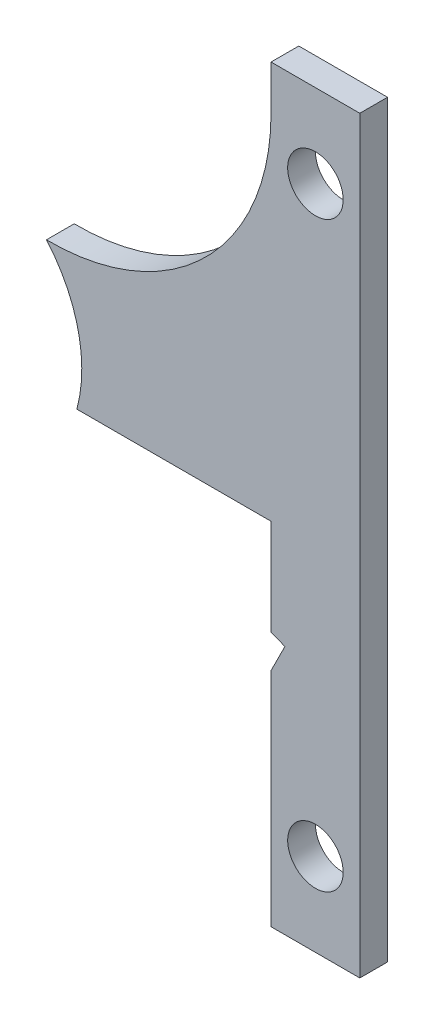
SolidWorks part; units mm, degrees
ref_plane "Front Plane" through (0, 0, 0) normal (0, 0, 1) x (1, 0, 0)
ref_plane "Top Plane" through (0, 0, 0) normal (0, 1, 0) x (1, 0, 0)
ref_plane "Right Plane" through (0, 0, 0) normal (1, 0, 0) x (0, 0, -1)
sketch "Sketch4" plane through (0, 0, 0) normal (0, 0, 1) x (1, 0, 0)
  line L9 (0, -70) -> (60, -70) construction
  line L10 (25, -6.6987) -> (60, -6.6987)
  line L11 (60, -24.0119) -> (60, -6.6987)
  line L12 (0, -70) -> (0, 0) construction
  line L13 (60, 57) -> (20, 57) construction
  line L15 (62.5, -25) -> (60, -24.0119)
  line L16 (60, -30) -> (62.5, -25)
  line L17 (60, -70) -> (60, -30)
  line L18 (76, -70) -> (60, -70)
  line L19 (76, 62) -> (76, -70)
  line L20 (60, 62) -> (76, 62) construction
  line L21 (60, 57) -> (60, 62)
  line L23 (0, 0) -> (25, -6.6987) construction
  line L24 (0, 0) -> (20, 16.782) construction
  line L25 (20, 16.782) -> (20, 57) construction
  line L26 (60, 62) -> (60, 65)
  line L27 (60, 65) -> (76, 65)
  line L28 (76, 65) -> (76, 62)
  circle A6 centre (0, 0) radius 25 construction
  arc A10 (25, -6.6987) -> (19.5134, 17.003) centre (0, 0) ccw
  arc A13 (60, 57) -> (19.5134, 17.003) centre (20, 57) cw
  dimension "D5" = 16
  dimension "D6" = 16
  dimension "D9" = 75
  dimension "D16" = 2.5
  dimension "D1" = 50
  dimension "D8" = 35
  dimension "D11" = 55
  dimension "D10" = 40
  dimension "D2" = 132
  dimension "D3" = 70
  dimension "D4" = 60
  dimension "D7" = 5
  dimension "D12" = 3
  dimension "D13" = 40
  dimension "D14" = 5
  dimension "D15" = 85
extrude "Boss-Extrude1" add sketch "Sketch4" along normal mid plane 5
hole_wizard "Ø10.0 (10) Diameter Hole1" positions "Sketch5" profile "Sketch6" hole size "Ø10.0" standard "AS" end condition through all
sketch "Sketch5" plane through (0, 0, 2.5) normal (0, 0, 1) x (1, 0, 0)
  line L0 (76, -70) -> (76, 65) construction
  line L1 (76, 65) -> (60, 65) construction
  line L2 (60, -70) -> (76, -70) construction
  point P0 (68, 50)
  point P7 (68, -55)
  dimension "D1" = 8
  dimension "D2" = 15
  dimension "D3" = 8
  dimension "D4" = 15
sketch "Sketch6" plane through (68, 50, 2.5) normal (1, 0, 0) x (0, -1, 0)
  line L0 (0, 0) -> (0, 5)
  line L1 (0, 5) -> (5, 5)
  line L2 (5, 5) -> (5, 0)
  line L5 (5, 0) -> (0, 0)
  line L11 (0, -6.35) -> (0, 107.95) construction
  dimension "Thru Hole Dia." = 10
  dimension "Thru Hole Depth" = 5
